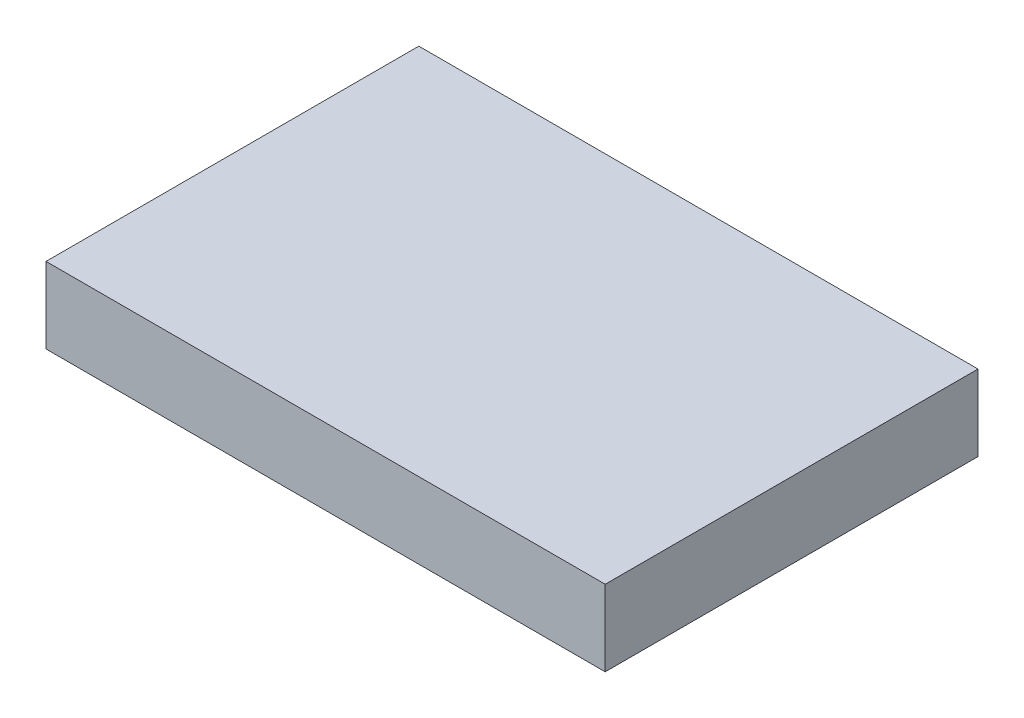
SolidWorks part; units mm, degrees
ref_plane "Front Plane" through (0, 0, 0) normal (0, 0, 1) x (1, 0, 0)
ref_plane "Top Plane" through (0, 0, 0) normal (0, 1, 0) x (1, 0, 0)
ref_plane "Right Plane" through (0, 0, 0) normal (1, 0, 0) x (0, 0, -1)
sketch "Sketch1" plane through (0, 0, 0) normal (0, 1, 0) x (1, 0, 0)
  line L1 (0, 0) -> (76.2, 0)
  line L2 (0, 0) -> (0, 50.8)
  line L3 (0, 50.8) -> (76.2, 50.8)
  line L4 (76.2, 0) -> (76.2, 50.8)
  dimension "D1" = 50.8
  dimension "D2" = 76.2
extrude "Boss-Extrude1" add sketch "Sketch1" along normal blind 10.3378
